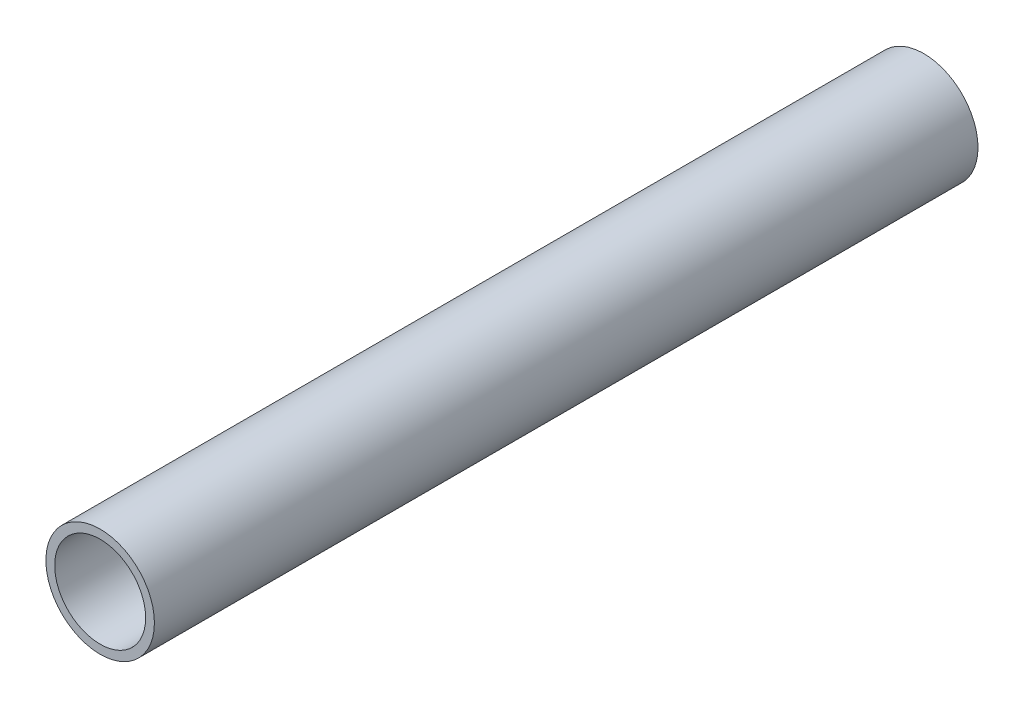
SolidWorks part; units mm, degrees
ref_plane "Front Plane" through (0, 0, 0) normal (0, 0, 1) x (1, 0, 0)
ref_plane "Top Plane" through (0, 0, 0) normal (0, 1, 0) x (1, 0, 0)
ref_plane "Right Plane" through (0, 0, 0) normal (1, 0, 0) x (0, 0, -1)
sketch "Sketch1" plane through (0, 0, 0) normal (0, 0, 1) x (1, 0, 0)
  circle A0 centre (0, 0) radius 30.3
  circle A1 centre (0, 0) radius 25.4
  dimension "D1" = 60.6
  dimension "D2" = 50.8
extrude "Boss-Extrude1" add sketch "Sketch1" along normal blind 460
